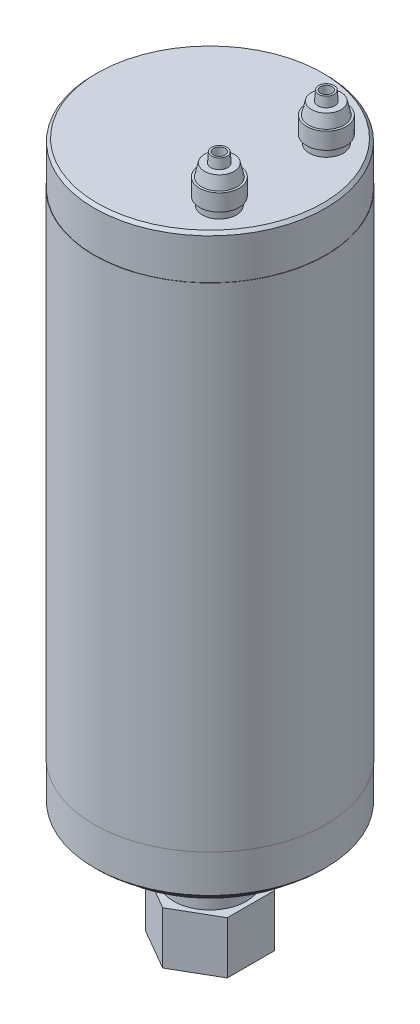
SolidWorks part; units mm, degrees
material "Plain Carbon Steel"
ref_plane "Front Plane" through (0, 0, 0) normal (0, 0, 1) x (1, 0, 0)
ref_plane "Top Plane" through (0, 0, 0) normal (0, 1, 0) x (1, 0, 0)
ref_plane "Right Plane" through (0, 0, 0) normal (1, 0, 0) x (0, 0, -1)
sketch "Sketch1" plane through (0, 0, 0) normal (1, 0, 0) x (0, 0, -1)
  line L0 (0, 104.5) -> (0, -104.5)
  line L1 (0, 104.5) -> (-39.9, 104.5)
  line L2 (-39.9, 104.5) -> (-39.9, 89.5)
  line L3 (-39.9, 89.5) -> (-40, 89.5)
  line L4 (-40, 89.5) -> (-40, -80.5)
  line L5 (-40, -80.5) -> (-39.9, -80.5)
  line L6 (-39.9, -80.5) -> (-39.9, -94.5)
  line L7 (-39.9, -94.5) -> (-35, -94.5)
  line L8 (-35, -94.5) -> (-35, -98.5)
  line L9 (-35, -98.5) -> (-21.965, -98.5)
  line L10 (-21.965, -98.5) -> (-19.925, -104.5)
  line L11 (-19.925, -104.5) -> (0, -104.5)
  dimension "D1" = 40
  dimension "D2" = 39.9
  dimension "D3" = 39.9
  dimension "D4" = 15
  dimension "D5" = 170
  dimension "D6" = 14
  dimension "D7" = 4
  dimension "D8" = 35
  dimension "D9" = 6
  dimension "D10" = 21.965
  dimension "D11" = 19.925
revolve "Revolve1" add sketch "Sketch1" angle 360 about L0
sketch "Sketch2" plane through (0, -104.5, 0) normal (0, -1, 0) x (1, 0, 0)
  circle A0 centre (0, 0) radius 12.5
  dimension "D1" = 25
extrude "Boss-Extrude1" add sketch "Sketch2" along normal blind 12.72
chamfer "Chamfer1" distance 1 angle 45 3 edges at (0, 104.5, 39.9) (0, -94.5, 39.9) (0, -98.5, 35)
sketch "Sketch3" plane through (0, -117.22, 0) normal (0, -1, 0) x (1, 0, 0)
  line L1 (0, 16.3101) -> (-14.125, 8.1551)
  line L2 (-14.125, 8.1551) -> (-14.125, -8.1551)
  line L3 (-14.125, -8.1551) -> (0, -16.3101)
  line L4 (0, -16.3101) -> (14.125, -8.1551)
  line L5 (14.125, -8.1551) -> (14.125, 8.1551)
  line L6 (14.125, 8.1551) -> (0, 16.3101)
  circle A0 centre (0, 0) radius 14.125 construction
  dimension "D1" = 28.25
extrude "Boss-Extrude2" add sketch "Sketch3" along normal blind 18
sketch "Sketch4" plane through (0, 0, 0) normal (1, 0, 0) x (0, 0, -1)
  line L0 (0, 258.155) -> (0, -49.1739) construction
  line L1 (-6, -135.22) -> (-6, -139.22)
  line L2 (8.1551, -135.22) -> (-8.1551, -135.22) construction
  line L3 (-6, -139.22) -> (-8, -139.22)
  line L4 (-8, -139.22) -> (-12, -135.22)
  line L5 (-12, -135.22) -> (-6, -135.22)
  dimension "D1" = 4
  dimension "D2" = 12
  dimension "D3" = 24
  dimension "D4" = 16
revolve "Revolve2" add sketch "Sketch4" angle 360 about L0
ref_plane "Plane1" through (21.67, 0, 0) normal (1, 0, 0) x (0, 0, -1)
sketch "Sketch6" plane through (21.67, 0, 0) normal (1, 0, 0) x (0, 0, -1)
  line L0 (18.45, 104.5) -> (18.45, 120.5) construction
  line L1 (38.9, 104.5) -> (-38.9, 104.5) construction
  line L2 (20.45, 104.5) -> (24.3, 104.5)
  line L3 (24.3, 104.5) -> (24.3, 107.26)
  line L4 (24.3, 107.26) -> (25.275, 107.26)
  line L5 (25.275, 107.26) -> (25.275, 113.02)
  line L6 (25.275, 113.02) -> (24.54, 113.02)
  line L7 (24.54, 113.02) -> (23.56, 117.19)
  line L8 (23.56, 117.19) -> (21.355, 117.19)
  line L9 (21.355, 117.19) -> (21.11, 120.5)
  line L10 (21.11, 120.5) -> (20.45, 120.5)
  line L11 (20.45, 120.5) -> (20.45, 104.5)
  line L12 (20.45, 120.5) -> (18.45, 120.5) construction
  line L13 (0, 150.816) -> (0, 113.02) construction
  dimension "D1" = 11.7
  dimension "D2" = 13.65
  dimension "D3" = 12.18
  dimension "D4" = 10.22
  dimension "D5" = 5.81
  dimension "D6" = 5.32
  dimension "D7" = 2.76
  dimension "D8" = 5.76
  dimension "D9" = 4.17
  dimension "D10" = 3.31
  dimension "D11" = 4
  dimension "D12" = 18.45
revolve "Revolve3" add sketch "Sketch6" angle 360 about L0
mirror "Mirror1" about plane through (0, 0, 0) normal (0, 0, 1) of "Revolve3"
